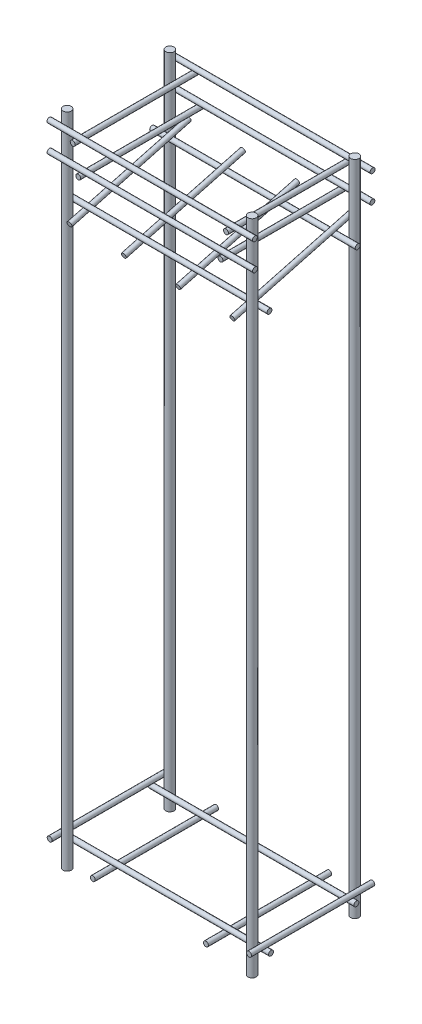
SolidWorks part; units mm, degrees
ref_plane "前视基准面" through (0, 0, 0) normal (0, 0, 1) x (1, 0, 0)
ref_plane "上视基准面" through (0, 0, 0) normal (0, 1, 0) x (1, 0, 0)
ref_plane "右视基准面" through (0, 0, 0) normal (1, 0, 0) x (0, 0, -1)
sketch "草图1" plane through (0, 0, 0) normal (0, 1, 0) x (1, 0, 0)
  line L0 (225, -125) -> (-225, -125) construction
  line L1 (250, -150) -> (-250, -150) construction
  line L2 (250, -150) -> (250, 150) construction
  line L3 (250, 150) -> (-250, 150) construction
  line L4 (-250, -150) -> (-250, 150) construction
  line L5 (250, -150) -> (-250, 150) construction
  line L6 (250, 150) -> (-250, -150) construction
  line L7 (0, -125) -> (0, 125) construction
  line L8 (-225, -125) -> (-225, 125) construction
  line L9 (-225, 125) -> (225, 125) construction
  line L10 (225, 125) -> (225, -125) construction
  circle A0 centre (-225, -125) radius 10
  circle A1 centre (225, -125) radius 10
  circle A2 centre (225, 125) radius 10
  circle A3 centre (-225, 125) radius 10
  point P0 (0, 0)
  point P9 (0, -125)
  point P12 (0, 0)
  dimension "D1" = 2
  dimension "D2" = 2
extrude "凸台-拉伸1" add sketch "草图1" along normal blind 1600
ref_plane "基准面4" through (-250, 0, 0) normal (1, 0, 0) x (0, 0, -1)
ref_plane "基准面5" through (0, 0, -150) normal (0, 0, 1) x (1, 0, 0)
sketch "草图2" plane through (0, 29.357, -150) normal (0, 0, 1) x (1, 0, 0)
  line L0 (0, 0) -> (0, 131.7184) construction
  circle A0 centre (-242.5297, 35.0632) radius 6
  circle A1 centre (242.5297, 35.0632) radius 6
  circle A2 centre (-137.6377, 4.2434) radius 6
  circle A3 centre (137.6377, 4.2434) radius 6
extrude "凸台-拉伸2" add sketch "草图2" along normal blind 300 separate body
sketch "草图3" plane through (-250, 0, 0) normal (1, 0, 0) x (0, 0, -1)
  line L0 (0, 0) -> (0, 79.1092) construction
  circle A0 centre (-103.9035, 47.3547) radius 6
  circle A1 centre (103.9035, 47.3547) radius 6
extrude "凸台-拉伸3" add sketch "草图3" along normal blind 500 separate body
sketch "草图5" plane through (-250, 0, 0) normal (1, 0, 0) x (0, 0, -1)
  line L0 (0.0364, -0.667) -> (0.0364, 94.436) construction
  circle A0 centre (-143.0864, 1572.5906) radius 6
  circle A1 centre (143.1591, 1572.5906) radius 6
extrude "凸台-拉伸4" add sketch "草图5" along normal blind 500 separate body
sketch "草图6" plane through (0, 0, -150) normal (0, 0, 1) x (1, 0, 0)
  line L0 (2.4084, -4.6828) -> (2.4084, 549.2156) construction
  line L1 (0, -165) -> (0, 165) construction
  line L2 (-186.5, 1558.9208) -> (186.5, 1558.9208) construction
  line L3 (-137.1548, 1561.4248) -> (236.2793, 1561.4248) construction
  circle A0 centre (-186.5, 1558.9208) radius 6
  circle A2 centre (186.5, 1558.9208) radius 6
extrude "凸台-拉伸5" add sketch "草图6" along normal blind 300 separate body
sketch "草图7" plane through (-250, 0, 0) normal (1, 0, 0) x (0, 0, -1)
  line L0 (0, 275) -> (0, -275) construction
  circle A0 centre (-142.693, 1506.8089) radius 6
  circle A1 centre (142.693, 1506.8089) radius 6
extrude "凸台-拉伸6" add sketch "草图7" along normal blind 500 separate body
sketch "草图9" plane through (0, 0, -150) normal (0, 0, 1) x (1, 0, 0)
  line L0 (0, -165) -> (0, 165) construction
  line L1 (-173, 1494.5446) -> (173, 1494.5446) construction
  circle A0 centre (-173, 1494.5446) radius 6
  circle A1 centre (173, 1494.5446) radius 6
extrude "凸台-拉伸7" add sketch "草图9" along normal blind 300 separate body
sketch "草图10" plane through (-250, 0, 0) normal (1, 0, 0) x (0, 0, -1)
  circle A0 centre (-107.6578, 1401.9253) radius 6
  circle A1 centre (106.9555, 1430.5072) radius 6
extrude "凸台-拉伸8" add sketch "草图10" along normal blind 500 separate body
ref_plane "基准面6" through (-200, 0, 0) normal (1, 0, 0) x (0, 0, -1)
sketch "草图11" plane through (-200, 0, 0) normal (1, 0, 0) x (0, 0, -1)
  line L0 (0, 275) -> (0, -275) construction
  line L5 (145.6606, 1455.9773) -> (-144.1172, 1378.3316) construction
  line L6 (145.6606, 1455.9773) -> (144.1077, 1461.7728)
  line L7 (144.1077, 1461.7728) -> (-145.6701, 1384.1271)
  line L8 (-144.1172, 1378.3316) -> (-145.6701, 1384.1271)
  line L9 (150, 1417.0494) -> (-150, 1423.0494) construction
  line L10 (150, 1423.0494) -> (-150, 1417.0494) construction
  line L11 (145.6606, 1455.9773) -> (-144.1172, 1378.3316)
  point P0 (0, 1420.0494)
revolve "旋转3" add sketch "草图11" angle 360 about L11
ref_plane "基准面7" through (-68, 0, 0) normal (1, 0, 0) x (0, 0, -1)
ref_plane "基准面8" through (64, 0, 0) normal (1, 0, 0) x (0, 0, -1)
ref_plane "基准面9" through (196, 0, 0) normal (1, 0, 0) x (0, 0, -1)
sketch "草图12" plane through (-68, 0, 0) normal (1, 0, 0) x (0, 0, -1)
  line L0 (145.6606, 1455.9773) -> (144.1077, 1461.7728) construction
  line L1 (145.6606, 1455.9773) -> (-144.1172, 1378.3316) construction
  line L2 (-144.1172, 1378.3316) -> (-145.6701, 1384.1271) construction
  line L3 (144.1077, 1461.7728) -> (-145.6701, 1384.1271) construction
  line L4 (145.6606, 1455.9773) -> (144.1077, 1461.7728)
  line L5 (145.6606, 1455.9773) -> (-144.1172, 1378.3316)
  line L6 (-144.1172, 1378.3316) -> (-145.6701, 1384.1271)
  line L7 (144.1077, 1461.7728) -> (-145.6701, 1384.1271)
sketch "草图13" plane through (64, 0, 0) normal (1, 0, 0) x (0, 0, -1)
  line L0 (-144.1172, 1378.3316) -> (-145.6701, 1384.1271) construction
  line L1 (145.6606, 1455.9773) -> (144.1077, 1461.7728) construction
  line L2 (145.6606, 1455.9773) -> (-144.1172, 1378.3316) construction
  line L3 (144.1077, 1461.7728) -> (-145.6701, 1384.1271) construction
  line L4 (-144.1172, 1378.3316) -> (-145.6701, 1384.1271)
  line L5 (145.6606, 1455.9773) -> (144.1077, 1461.7728)
  line L6 (145.6606, 1455.9773) -> (-144.1172, 1378.3316)
  line L7 (144.1077, 1461.7728) -> (-145.6701, 1384.1271)
sketch "草图14" plane through (196, 0, 0) normal (1, 0, 0) x (0, 0, -1)
  line L0 (-144.1172, 1378.3316) -> (-145.6701, 1384.1271) construction
  line L1 (145.6606, 1455.9773) -> (144.1077, 1461.7728) construction
  line L2 (145.6606, 1455.9773) -> (-144.1172, 1378.3316) construction
  line L3 (144.1077, 1461.7728) -> (-145.6701, 1384.1271) construction
  line L4 (-144.1172, 1378.3316) -> (-145.6701, 1384.1271)
  line L5 (145.6606, 1455.9773) -> (144.1077, 1461.7728)
  line L6 (145.6606, 1455.9773) -> (-144.1172, 1378.3316)
  line L7 (144.1077, 1461.7728) -> (-145.6701, 1384.1271)
revolve "旋转4" add sketch "草图12" angle 360 about L5
revolve "旋转5" add sketch "草图13" angle 360 about L6
revolve "旋转6" add sketch "草图14" angle 360 about L6
